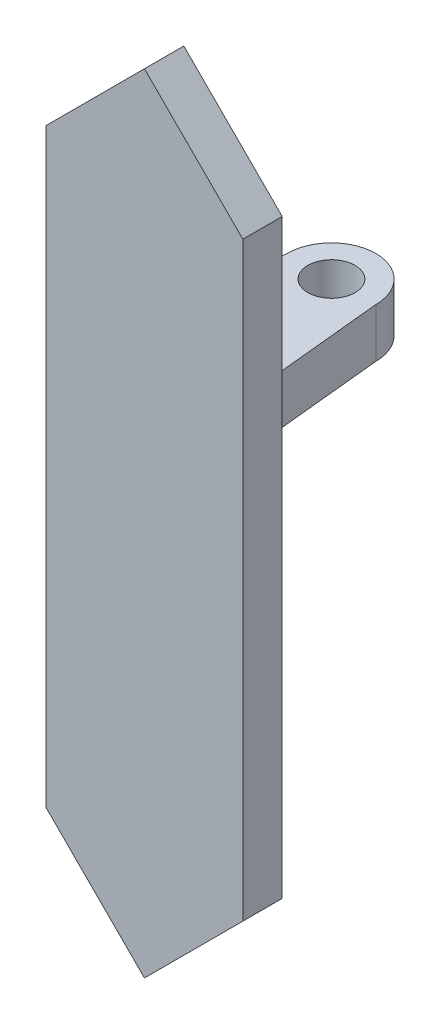
SolidWorks part; units mm, degrees
ref_plane "前视基准面" through (0, 0, 0) normal (0, 0, 1) x (1, 0, 0)
ref_plane "上视基准面" through (0, 0, 0) normal (0, 1, 0) x (1, 0, 0)
ref_plane "右视基准面" through (0, 0, 0) normal (1, 0, 0) x (0, 0, -1)
sketch "草图1" plane through (0, 0, 0) normal (0, 0, 1) x (1, 0, 0)
  line L2 (0.1473, 10) -> (0.1473, 70)
  line L4 (20.1473, 10) -> (20.1473, 70)
  line L5 (0.1473, 70) -> (10.1473, 80)
  line L6 (10.1473, 80) -> (20.1473, 70)
  line L8 (10.1473, 0) -> (20.1473, 10)
  line L9 (0.1473, 10) -> (10.1473, 0)
extrude "凸台-拉伸1" add sketch "草图1" along normal blind 4 contours L2 L9 L8 L4 L6 L5
sketch "草图2" plane through (0, 0, 0) normal (0, 0, -1) x (-1, 0, 0)
  line L0 (-10.1473, 52) -> (-10.1473, 80)
  line L5 (-16.1473, 52) -> (-4.1473, 52)
  line L6 (-16.1473, 52) -> (-16.1473, 47)
  line L7 (-16.1473, 47) -> (-4.1473, 47)
  line L8 (-4.1473, 52) -> (-4.1473, 47)
  line L9 (-16.1473, 52) -> (-4.1473, 47) construction
  line L10 (-16.1473, 47) -> (-4.1473, 52) construction
  point P8 (-10.1473, 49.5)
  dimension "D1" = 28
extrude "凸台-拉伸2" add sketch "草图2" along normal blind 20 contours L8 L5 L6 L7
sketch "草图6" plane through (0, 47, 0) normal (0, -1, 0) x (1, 0, 0)
  line L3 (5.6473, -15) -> (4.1473, 0)
  line L4 (14.6473, -15) -> (16.1473, 0)
  circle A0 centre (10.1473, -15) radius 4.5
  circle A1 centre (10.1473, -15) radius 2.4
  line M5 (4.1473, 0) -> (4.1473, -20)
  line M6 (4.1473, -20) -> (16.1473, -20)
  line M7 (16.1473, -20) -> (16.1473, 0)
extrude "切除-拉伸5" cut sketch "草图6" against normal blind 21 contours A1 | A0 L3 L4 M5 M6 M7
